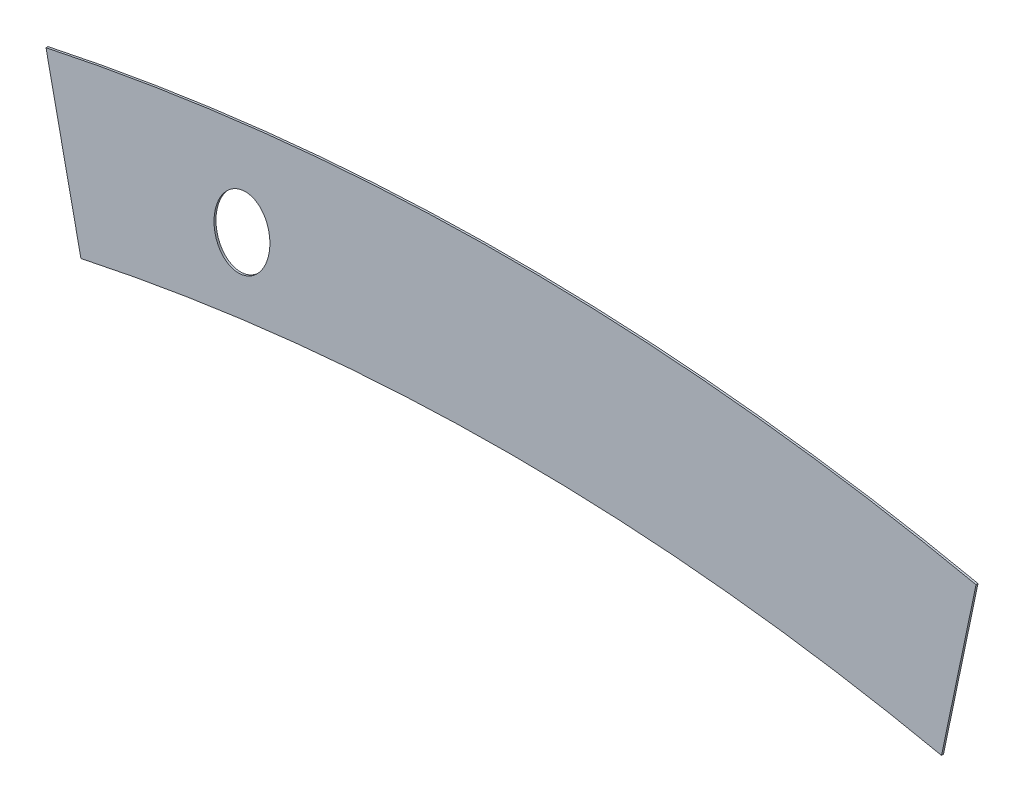
SolidWorks part; units mm, degrees
material "6061 Alloy"
ref_plane "front" through (0, 0, 0) normal (0, 0, 1) x (1, 0, 0)
ref_plane "top" through (0, 0, 0) normal (0, 1, 0) x (1, 0, 0)
ref_plane "right" through (0, 0, 0) normal (1, 0, 0) x (0, 0, -1)
sketch "Sketch1" plane through (0, 0, 0) normal (0, 0, 1) x (1, 0, 0)
  line L0 (0, 0) -> (0, -273.05) construction
  line L1 (0, 0) -> (383.281, 0) construction
  line L2 (-752.475, -79.5348) -> (-695.96, -346.6728)
  line L3 (752.475, -79.5348) -> (696.595, -346.8088)
  line L4 (-403.225, -22.6575) -> (-461.0601, -305.159) construction
  arc A0 (752.475, -79.5348) -> (-752.475, -79.5348) centre (0, -3599.3324) ccw
  arc A1 (696.595, -346.8088) -> (-695.96, -346.6728) centre (0, -3599.3324) ccw
  ellipse E0 centre (-435.3831, -179.737) end of major axis (-447.4822, -238.8362) minor radius 44.45
  dimension "D1" = 3599.3324
  dimension "D5" = 11.57
  dimension "D7" = 88.9
  dimension "D2" = 1504.95
  dimension "D3" = 273.05
  dimension "D4" = 695.96
  dimension "D6" = 403.225
  dimension "D8" = 120.65
  dimension "D9" = 160.3375
  dimension "D10" = 752.475
  dimension "D13" = 696.595
extrude "Base-Extrude" add sketch "Sketch1" against normal blind 3.175
